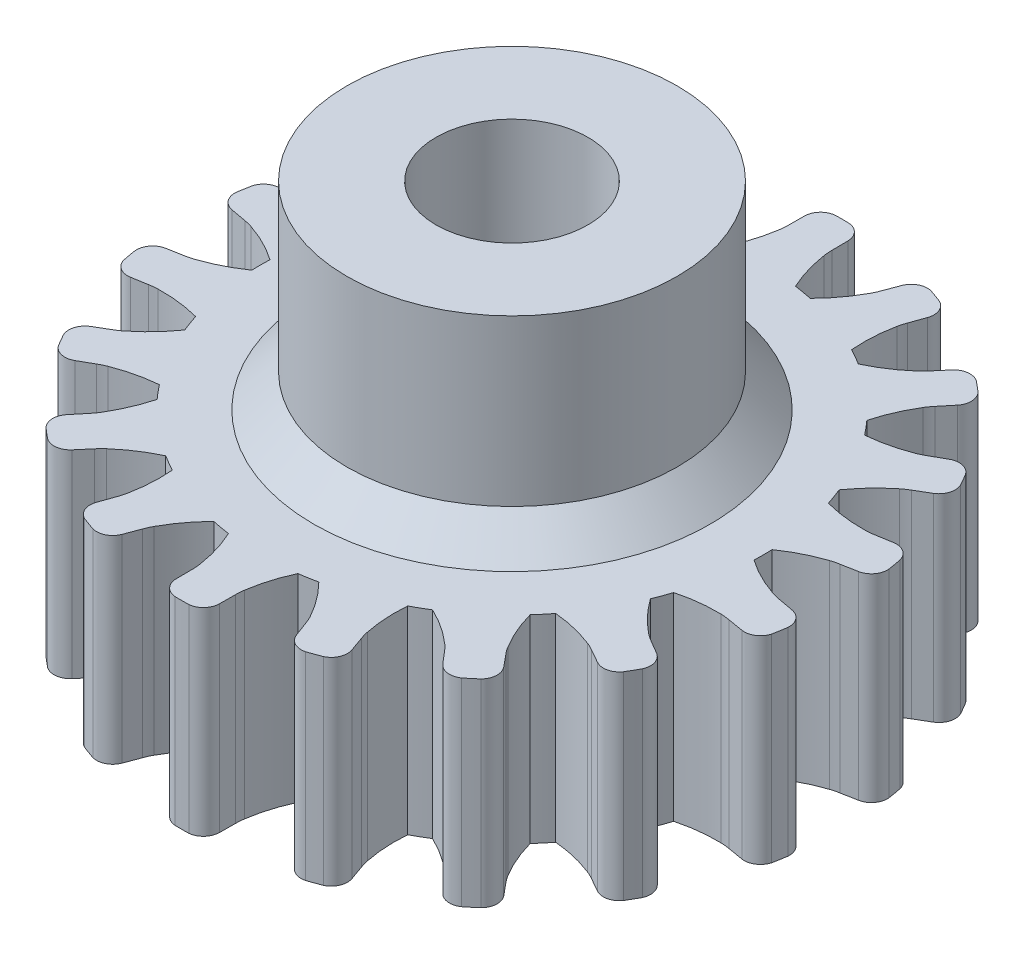
SolidWorks part; units mm, degrees
ref_plane "Front Plane" through (0, 0, 0) normal (0, 0, 1) x (1, 0, 0)
ref_plane "Top Plane" through (0, 0, 0) normal (0, 1, 0) x (1, 0, 0)
ref_plane "Right Plane" through (0, 0, 0) normal (1, 0, 0) x (0, 0, -1)
sketch "Sketch1" plane through (0, 0, 0) normal (0, 1, 0) x (1, 0, 0)
  line L0 (-1.05, 0) -> (1.05, 0)
  line L1 (-0.165, -2.4651) -> (0.165, -2.4651)
  line L2 (-0.655, -1.9793) -> (-0.6591, -1.4994)
  line L3 (0, 0) -> (0, -2.4651) construction
  line L4 (0.655, -1.9793) -> (0.6591, -1.4994)
  line L5 (-3.5637, 0.8135) -> (-1.5904, 0.0953)
  line L6 (-3.5753, -1.8056) -> (-3.2652, -1.9185)
  line L7 (-3.8695, -1.1815) -> (-3.7092, -0.7291)
  line L8 (-2.6386, -1.6296) -> (-2.4705, -1.1799)
  line L9 (-2.5771, 0.4544) -> (-3.4202, -1.8621) construction
  line L10 (-5.6477, 2.4377) -> (-4.039, 1.0879)
  line L11 (-6.5543, -0.0195) -> (-6.3015, -0.2317)
  line L12 (-6.6173, 0.6676) -> (-6.312, 1.0379)
  line L13 (-5.6139, -0.1745) -> (-5.3022, 0.1906)
  line L14 (-4.8433, 1.7628) -> (-6.4279, -0.1256) construction
  line L15 (-7.0504, 4.6768) -> (-6.0004, 2.8581)
  line L16 (-8.7428, 2.6777) -> (-8.5778, 2.392)
  line L17 (-8.567, 3.345) -> (-8.1534, 3.5885)
  line L18 (-7.912, 2.2105) -> (-7.4943, 2.447)
  line L19 (-6.5254, 3.7674) -> (-8.6603, 2.5349) construction
  line L20 (-7.6027, 7.2605) -> (-7.238, 5.1924)
  line L21 (-9.8767, 5.9609) -> (-9.8194, 5.6359)
  line L22 (-9.4834, 6.5278) -> (-9.0114, 6.6151)
  line L23 (-9.2559, 5.2377) -> (-8.7825, 5.317)
  line L24 (-7.4204, 6.2264) -> (-9.8481, 5.7984) construction
  line L25 (-7.238, 9.8773) -> (-7.6027, 7.8092)
  line L26 (-9.8194, 9.4338) -> (-9.8767, 9.1088)
  line L27 (-9.2559, 9.832) -> (-8.7825, 9.7527)
  line L28 (-9.4834, 8.5419) -> (-9.0114, 8.4546)
  line L29 (-7.4204, 8.8433) -> (-9.8481, 9.2713) construction
  line L30 (-6.0004, 12.2116) -> (-7.0504, 10.3929)
  line L31 (-8.5778, 12.6777) -> (-8.7428, 12.392)
  line L32 (-7.912, 12.8592) -> (-7.4943, 12.6227)
  line L33 (-8.567, 11.7247) -> (-8.1534, 11.4812)
  line L34 (-6.5254, 11.3023) -> (-8.6603, 12.5349) construction
  line L35 (-4.039, 13.9818) -> (-5.6477, 12.632)
  line L36 (-6.3015, 15.3014) -> (-6.5543, 15.0892)
  line L37 (-5.6139, 15.2442) -> (-5.3022, 14.8791)
  line L38 (-6.6173, 14.4021) -> (-6.312, 14.0318)
  line L39 (-4.8433, 13.3069) -> (-6.4279, 15.1953) construction
  line L40 (-1.5904, 14.9744) -> (-3.5637, 14.2562)
  line L41 (-3.2652, 16.9882) -> (-3.5753, 16.8753)
  line L42 (-2.6386, 16.6993) -> (-2.4705, 16.2496)
  line L43 (-3.8695, 16.2512) -> (-3.7092, 15.7988)
  line L44 (-2.5771, 14.6153) -> (-3.4202, 16.9318) construction
  line L45 (1.05, 15.0697) -> (-1.05, 15.0697)
  line L46 (0.165, 17.5349) -> (-0.165, 17.5349)
  line L47 (0.655, 17.049) -> (0.6591, 16.5691)
  line L48 (-0.655, 17.049) -> (-0.6591, 16.5691)
  line L49 (0, 15.0697) -> (0, 17.5349) construction
  line L50 (3.5637, 14.2562) -> (1.5904, 14.9744)
  line L51 (3.5753, 16.8753) -> (3.2652, 16.9882)
  line L52 (3.8695, 16.2512) -> (3.7092, 15.7988)
  line L53 (2.6386, 16.6993) -> (2.4705, 16.2496)
  line L54 (2.5771, 14.6153) -> (3.4202, 16.9318) construction
  line L55 (5.6477, 12.632) -> (4.039, 13.9818)
  line L56 (6.5543, 15.0892) -> (6.3015, 15.3014)
  line L57 (6.6173, 14.4021) -> (6.312, 14.0318)
  line L58 (5.6139, 15.2442) -> (5.3022, 14.8791)
  line L59 (4.8433, 13.3069) -> (6.4279, 15.1953) construction
  line L60 (7.0504, 10.3929) -> (6.0004, 12.2116)
  line L61 (8.7428, 12.392) -> (8.5778, 12.6777)
  line L62 (8.567, 11.7247) -> (8.1534, 11.4812)
  line L63 (7.912, 12.8592) -> (7.4943, 12.6227)
  line L64 (6.5254, 11.3023) -> (8.6603, 12.5349) construction
  line L65 (7.6027, 7.8092) -> (7.238, 9.8773)
  line L66 (9.8767, 9.1088) -> (9.8194, 9.4338)
  line L67 (9.4834, 8.5419) -> (9.0114, 8.4546)
  line L68 (9.2559, 9.832) -> (8.7825, 9.7527)
  line L69 (7.4204, 8.8433) -> (9.8481, 9.2713) construction
  line L70 (7.238, 5.1924) -> (7.6027, 7.2605)
  line L71 (9.8194, 5.6359) -> (9.8767, 5.9609)
  line L72 (9.2559, 5.2377) -> (8.7825, 5.317)
  line L73 (9.4834, 6.5278) -> (9.0114, 6.6151)
  line L74 (7.4204, 6.2264) -> (9.8481, 5.7984) construction
  line L75 (6.0004, 2.8581) -> (7.0504, 4.6768)
  line L76 (8.5778, 2.392) -> (8.7428, 2.6777)
  line L77 (7.912, 2.2105) -> (7.4943, 2.447)
  line L78 (8.567, 3.345) -> (8.1534, 3.5885)
  line L79 (6.5254, 3.7674) -> (8.6603, 2.5349) construction
  line L80 (4.039, 1.0879) -> (5.6477, 2.4377)
  line L81 (6.3015, -0.2317) -> (6.5543, -0.0195)
  line L82 (5.6139, -0.1745) -> (5.3022, 0.1906)
  line L83 (6.6173, 0.6676) -> (6.312, 1.0379)
  line L84 (4.8433, 1.7628) -> (6.4279, -0.1256) construction
  line L85 (1.5904, 0.0953) -> (3.5637, 0.8135)
  line L86 (3.2652, -1.9185) -> (3.5753, -1.8056)
  line L87 (2.6386, -1.6296) -> (2.4705, -1.1799)
  line L88 (3.8695, -1.1815) -> (3.7092, -0.7291)
  line L89 (2.5771, 0.4544) -> (3.4202, -1.8621) construction
  arc A0 (-1.05, 0) -> (-0.6774, -1.24) centre (-5.1479, -1.9072) cw
  arc A1 (-0.6774, -1.24) -> (-0.6591, -1.4994) centre (-2.339, -1.488) cw
  arc A2 (0.655, -1.9793) -> (0.165, -2.4651) centre (0.165, -1.9751) cw
  arc A3 (-0.655, -1.9793) -> (-0.165, -2.4651) centre (-0.165, -1.9751) ccw
  arc A4 (0.6774, -1.24) -> (0.6591, -1.4994) centre (2.339, -1.488) ccw
  arc A5 (1.05, 0) -> (0.6774, -1.24) centre (5.1479, -1.9072) ccw
  circle A6 centre (0, 7.5349) radius 10
  arc A7 (-3.5637, 0.8135) -> (-3.6378, -0.4791) centre (-8.0668, 0.4229) cw
  arc A8 (-3.6378, -0.4791) -> (-3.7092, -0.7291) centre (-5.284, -0.1438) cw
  arc A9 (-2.6386, -1.6296) -> (-3.2652, -1.9185) centre (-3.0976, -1.4581) cw
  arc A10 (-3.8695, -1.1815) -> (-3.5753, -1.8056) centre (-3.4077, -1.3452) ccw
  arc A11 (-2.3646, -0.9425) -> (-2.4705, -1.1799) centre (-0.888, -1.7438) ccw
  arc A12 (-1.5904, 0.0953) -> (-2.3646, -0.9425) centre (1.6081, -3.0985) ccw
  arc A13 (-5.6477, 2.4377) -> (-6.1593, 1.2484) centre (-10.0128, 3.6109) cw
  arc A14 (-6.1593, 1.2484) -> (-6.312, 1.0379) centre (-7.5916, 2.1265) cw
  arc A15 (-5.6139, -0.1745) -> (-6.3015, -0.2317) centre (-5.9865, 0.1437) cw
  arc A16 (-6.6173, 0.6676) -> (-6.5543, -0.0195) centre (-6.2393, 0.3558) ccw
  arc A17 (-5.1214, 0.3775) -> (-5.3022, 0.1906) centre (-4.008, -0.8805) ccw
  arc A18 (-4.039, 1.0879) -> (-5.1214, 0.3775) centre (-2.1257, -3.0072) ccw
  arc A19 (-7.0504, 4.6768) -> (-7.938, 3.7341) centre (-10.751, 7.2721) cw
  arc A20 (-7.938, 3.7341) -> (-8.1534, 3.5885) centre (-8.9835, 5.0491) cw
  arc A21 (-7.912, 2.2105) -> (-8.5778, 2.392) centre (-8.1534, 2.637) cw
  arc A22 (-8.567, 3.345) -> (-8.7428, 2.6777) centre (-8.3184, 2.9227) ccw
  arc A23 (-7.2605, 2.5607) -> (-7.4943, 2.447) centre (-6.6445, 0.9978) ccw
  arc A24 (-6.0004, 2.8581) -> (-7.2605, 2.5607) centre (-5.6031, -1.6444) ccw
  arc A25 (-7.6027, 7.2605) -> (-8.7592, 6.6783) centre (-10.1925, 10.965) cw
  arc A26 (-8.7592, 6.6783) -> (-9.0114, 6.6151) centre (-9.2919, 8.2716) cw
  arc A27 (-9.2559, 5.2377) -> (-9.8194, 5.6359) centre (-9.3369, 5.721) cw
  arc A28 (-9.4834, 6.5278) -> (-9.8767, 5.9609) centre (-9.3942, 6.0459) ccw
  arc A29 (-8.5239, 5.344) -> (-8.7825, 5.317) centre (-8.4796, 3.6645) ccw
  arc A30 (-7.238, 5.1924) -> (-8.5239, 5.344) centre (-8.4047, 0.8255) ccw
  arc A31 (-7.238, 9.8773) -> (-8.5239, 9.7257) centre (-8.4047, 14.2442) cw
  arc A32 (-8.5239, 9.7257) -> (-8.7825, 9.7527) centre (-8.4796, 11.4052) cw
  arc A33 (-9.4834, 8.5419) -> (-9.8767, 9.1088) centre (-9.3942, 9.0238) cw
  arc A34 (-9.2559, 9.832) -> (-9.8194, 9.4338) centre (-9.3369, 9.3487) ccw
  arc A35 (-8.7592, 8.3914) -> (-9.0114, 8.4546) centre (-9.2919, 6.7981) ccw
  arc A36 (-7.6027, 7.8092) -> (-8.7592, 8.3914) centre (-10.1925, 4.1047) ccw
  arc A37 (-6.0004, 12.2116) -> (-7.2605, 12.509) centre (-5.6031, 16.7141) cw
  arc A38 (-7.2605, 12.509) -> (-7.4943, 12.6227) centre (-6.6445, 14.0719) cw
  arc A39 (-8.567, 11.7247) -> (-8.7428, 12.392) centre (-8.3184, 12.147) cw
  arc A40 (-7.912, 12.8592) -> (-8.5778, 12.6777) centre (-8.1534, 12.4327) ccw
  arc A41 (-7.938, 11.3356) -> (-8.1534, 11.4812) centre (-8.9835, 10.0206) ccw
  arc A42 (-7.0504, 10.3929) -> (-7.938, 11.3356) centre (-10.751, 7.7976) ccw
  arc A43 (-4.039, 13.9818) -> (-5.1214, 14.6922) centre (-2.1257, 18.0769) cw
  arc A44 (-5.1214, 14.6922) -> (-5.3022, 14.8791) centre (-4.008, 15.9502) cw
  arc A45 (-6.6173, 14.4021) -> (-6.5543, 15.0892) centre (-6.2393, 14.7139) cw
  arc A46 (-5.6139, 15.2442) -> (-6.3015, 15.3014) centre (-5.9865, 14.926) ccw
  arc A47 (-6.1593, 13.8213) -> (-6.312, 14.0318) centre (-7.5916, 12.9432) ccw
  arc A48 (-5.6477, 12.632) -> (-6.1593, 13.8213) centre (-10.0128, 11.4588) ccw
  arc A49 (-1.5904, 14.9744) -> (-2.3646, 16.0122) centre (1.6081, 18.1682) cw
  arc A50 (-2.3646, 16.0122) -> (-2.4705, 16.2496) centre (-0.888, 16.8135) cw
  arc A51 (-3.8695, 16.2512) -> (-3.5753, 16.8753) centre (-3.4077, 16.4149) cw
  arc A52 (-2.6386, 16.6993) -> (-3.2652, 16.9882) centre (-3.0976, 16.5278) ccw
  arc A53 (-3.6378, 15.5488) -> (-3.7092, 15.7988) centre (-5.284, 15.2135) ccw
  arc A54 (-3.5637, 14.2562) -> (-3.6378, 15.5488) centre (-8.0668, 14.6468) ccw
  arc A55 (1.05, 15.0697) -> (0.6774, 16.3097) centre (5.1479, 16.9769) cw
  arc A56 (0.6774, 16.3097) -> (0.6591, 16.5691) centre (2.339, 16.5577) cw
  arc A57 (-0.655, 17.049) -> (-0.165, 17.5349) centre (-0.165, 17.0449) cw
  arc A58 (0.655, 17.049) -> (0.165, 17.5349) centre (0.165, 17.0449) ccw
  arc A59 (-0.6774, 16.3097) -> (-0.6591, 16.5691) centre (-2.339, 16.5577) ccw
  arc A60 (-1.05, 15.0697) -> (-0.6774, 16.3097) centre (-5.1479, 16.9769) ccw
  arc A61 (3.5637, 14.2562) -> (3.6378, 15.5488) centre (8.0668, 14.6468) cw
  arc A62 (3.6378, 15.5488) -> (3.7092, 15.7988) centre (5.284, 15.2135) cw
  arc A63 (2.6386, 16.6993) -> (3.2652, 16.9882) centre (3.0976, 16.5278) cw
  arc A64 (3.8695, 16.2512) -> (3.5753, 16.8753) centre (3.4077, 16.4149) ccw
  arc A65 (2.3646, 16.0122) -> (2.4705, 16.2496) centre (0.888, 16.8135) ccw
  arc A66 (1.5904, 14.9744) -> (2.3646, 16.0122) centre (-1.6081, 18.1682) ccw
  arc A67 (5.6477, 12.632) -> (6.1593, 13.8213) centre (10.0128, 11.4588) cw
  arc A68 (6.1593, 13.8213) -> (6.312, 14.0318) centre (7.5916, 12.9432) cw
  arc A69 (5.6139, 15.2442) -> (6.3015, 15.3014) centre (5.9865, 14.926) cw
  arc A70 (6.6173, 14.4021) -> (6.5543, 15.0892) centre (6.2393, 14.7139) ccw
  arc A71 (5.1214, 14.6922) -> (5.3022, 14.8791) centre (4.008, 15.9502) ccw
  arc A72 (4.039, 13.9818) -> (5.1214, 14.6922) centre (2.1257, 18.0769) ccw
  arc A73 (7.0504, 10.3929) -> (7.938, 11.3356) centre (10.751, 7.7976) cw
  arc A74 (7.938, 11.3356) -> (8.1534, 11.4812) centre (8.9835, 10.0206) cw
  arc A75 (7.912, 12.8592) -> (8.5778, 12.6777) centre (8.1534, 12.4327) cw
  arc A76 (8.567, 11.7247) -> (8.7428, 12.392) centre (8.3184, 12.147) ccw
  arc A77 (7.2605, 12.509) -> (7.4943, 12.6227) centre (6.6445, 14.0719) ccw
  arc A78 (6.0004, 12.2116) -> (7.2605, 12.509) centre (5.6031, 16.7141) ccw
  arc A79 (7.6027, 7.8092) -> (8.7592, 8.3914) centre (10.1925, 4.1047) cw
  arc A80 (8.7592, 8.3914) -> (9.0114, 8.4546) centre (9.2919, 6.7981) cw
  arc A81 (9.2559, 9.832) -> (9.8194, 9.4338) centre (9.3369, 9.3487) cw
  arc A82 (9.4834, 8.5419) -> (9.8767, 9.1088) centre (9.3942, 9.0238) ccw
  arc A83 (8.5239, 9.7257) -> (8.7825, 9.7527) centre (8.4796, 11.4052) ccw
  arc A84 (7.238, 9.8773) -> (8.5239, 9.7257) centre (8.4047, 14.2442) ccw
  arc A85 (7.238, 5.1924) -> (8.5239, 5.344) centre (8.4047, 0.8255) cw
  arc A86 (8.5239, 5.344) -> (8.7825, 5.317) centre (8.4796, 3.6645) cw
  arc A87 (9.4834, 6.5278) -> (9.8767, 5.9609) centre (9.3942, 6.0459) cw
  arc A88 (9.2559, 5.2377) -> (9.8194, 5.6359) centre (9.3369, 5.721) ccw
  arc A89 (8.7592, 6.6783) -> (9.0114, 6.6151) centre (9.2919, 8.2716) ccw
  arc A90 (7.6027, 7.2605) -> (8.7592, 6.6783) centre (10.1925, 10.965) ccw
  arc A91 (6.0004, 2.8581) -> (7.2605, 2.5607) centre (5.6031, -1.6444) cw
  arc A92 (7.2605, 2.5607) -> (7.4943, 2.447) centre (6.6445, 0.9978) cw
  arc A93 (8.567, 3.345) -> (8.7428, 2.6777) centre (8.3184, 2.9227) cw
  arc A94 (7.912, 2.2105) -> (8.5778, 2.392) centre (8.1534, 2.637) ccw
  arc A95 (7.938, 3.7341) -> (8.1534, 3.5885) centre (8.9835, 5.0491) ccw
  arc A96 (7.0504, 4.6768) -> (7.938, 3.7341) centre (10.751, 7.2721) ccw
  arc A97 (4.039, 1.0879) -> (5.1214, 0.3775) centre (2.1257, -3.0072) cw
  arc A98 (5.1214, 0.3775) -> (5.3022, 0.1906) centre (4.008, -0.8805) cw
  arc A99 (6.6173, 0.6676) -> (6.5543, -0.0195) centre (6.2393, 0.3558) cw
  arc A100 (5.6139, -0.1745) -> (6.3015, -0.2317) centre (5.9865, 0.1437) ccw
  arc A101 (6.1593, 1.2484) -> (6.312, 1.0379) centre (7.5916, 2.1265) ccw
  arc A102 (5.6477, 2.4377) -> (6.1593, 1.2484) centre (10.0128, 3.6109) ccw
  arc A103 (1.5904, 0.0953) -> (2.3646, -0.9425) centre (-1.6081, -3.0985) cw
  arc A104 (2.3646, -0.9425) -> (2.4705, -1.1799) centre (0.888, -1.7438) cw
  arc A105 (3.8695, -1.1815) -> (3.5753, -1.8056) centre (3.4077, -1.3452) cw
  arc A106 (2.6386, -1.6296) -> (3.2652, -1.9185) centre (3.0976, -1.4581) ccw
  arc A107 (3.6378, -0.4791) -> (3.7092, -0.7291) centre (5.284, -0.1438) ccw
  arc A108 (3.5637, 0.8135) -> (3.6378, -0.4791) centre (8.0668, 0.4229) ccw
  circle A109 centre (0, 7.5349) radius 7.6077
  point P329 (0, 7.5349)
  dimension "D1" = 0.49
  dimension "D4" = 1.68
  dimension "D5" = 4.52
  dimension "D6" = 0.165
  dimension "D10" = 20
  dimension "D2" = 0.69
  dimension "D3" = 0.48
  dimension "D7" = 0.26
  dimension "D8" = 1.24
  dimension "D9" = 1.05
  dimension "D11" = 18
extrude "Boss-Extrude1" add sketch "Sketch1" along normal blind 6 contours A109 A31 A32 L27 A34 A6 A33 L28 A35 A36 | L25 A109 | L0 A109 L85 L80 L75 L70 L65 L60 L55 L50 L45 L40 L35 L30 L25 L20 L15 L10 L5 | A109 A37 A38 L32 A40 A6 A39 L33 A41 A42 | L30 A109 | A109 A43 A44 L37 A46 A6 A45 L38 A47 A48 | A109 A49 A50 L42 A52 A6 A51 L43 A53 A54 | A109 A55 A56 L47 A58 A6 A57 L48 A59 A60 | A109 A61 A62 L52 A64 A6 A63 L53 A65 A66 | A109 A67 A68 L57 A70 A6 A69 L58 A71 A72 | A109 A73 A74 L62 A76 A6 A75 L63 A77 A78 | A109 A79 A80 L67 A82 A6 A81 L68 A83 A84 | A109 A85 A86 L72 A88 A6 A87 L73 A89 A90 | A109 A91 A92 L77 A94 A6 A93 L78 A95 A96 | A109 A97 A98 L82 A100 A6 A99 L83 A101 A102 | A109 A103 A104 L87 A106 A6 A105 L88 A107 A108 | A109 A0 A1 L2 A3 A6 A2 L4 A4 A5 | A109 A7 A8 L7 A10 A6 A9 L8 A11 A12 | A109 A25 A26 L22 A28 A6 A27 L23 A29 A30 | A109 A19 A20 L17 A22 A6 A21 L18 A23 A24 | A109 A13 A14 L12 A16 A6 A15 L13 A17 A18
sketch "Sketch2" plane through (0, 6, 0) normal (0, 1, 0) x (1, 0, 0)
  circle A0 centre (0, 7.5349) radius 7.6077 construction
  circle A1 centre (0, 7.5349) radius 7.6077
  circle A2 centre (0, 7.5349) radius 5
  dimension "D1" = 10
extrude "Boss-Extrude2" add sketch "Sketch2" along normal blind 6 contours A2
chamfer "Chamfer1" distance 1 angle 45 1 edges at (0, 6, -2.5349)
sketch "Sketch3" plane through (0, 12, 0) normal (0, 1, 0) x (1, 0, 0)
  circle A0 centre (0, 7.5349) radius 2.3
  dimension "D1" = 4.6
extrude "Cut-Extrude1" cut sketch "Sketch3" against normal blind 4
